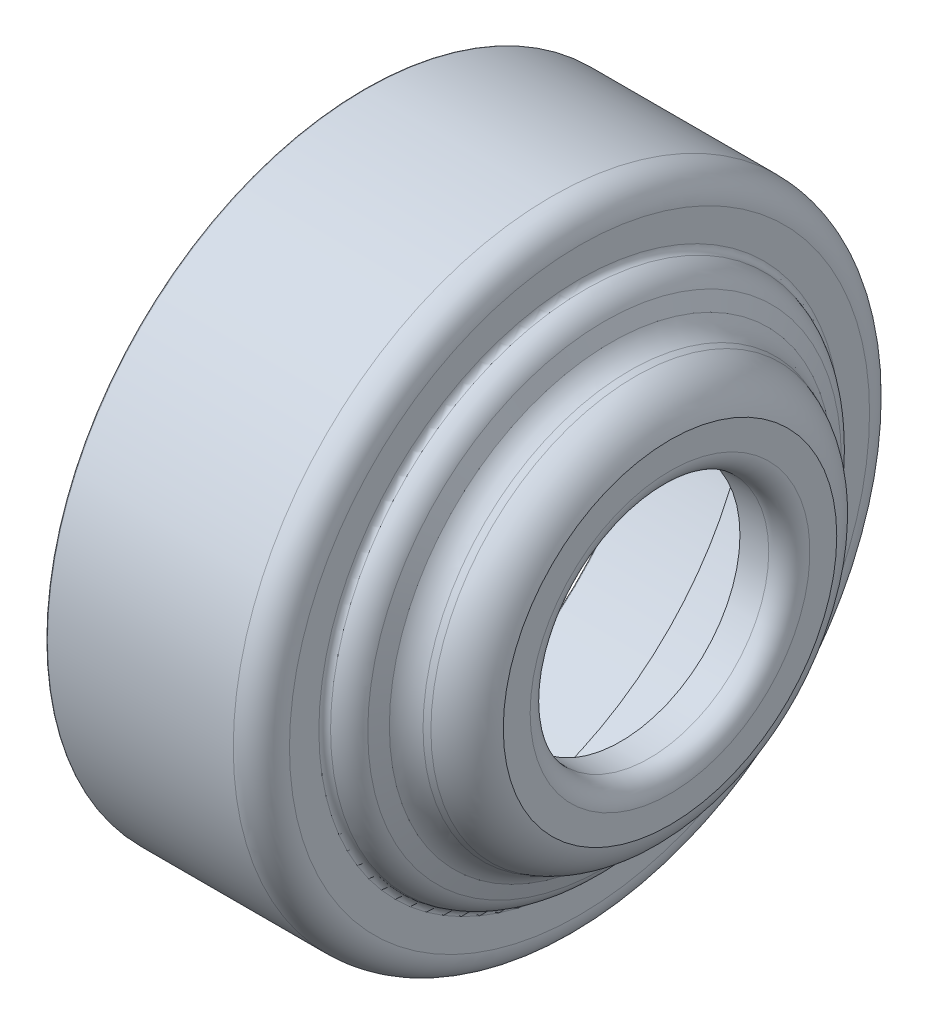
SolidWorks part; units mm, degrees
ref_plane "前视基准面" through (0, 0, 0) normal (0, 0, 1) x (1, 0, 0)
ref_plane "上视基准面" through (0, 0, 0) normal (0, 1, 0) x (1, 0, 0)
ref_plane "右视基准面" through (0, 0, 0) normal (1, 0, 0) x (0, 0, -1)
sketch "草图1" plane through (0, 0, 0) normal (0, 0, 1) x (1, 0, 0)
  line L0 (-28.9725, 0) -> (27.6414, 0) construction
  line L1 (0, 33.7643) -> (0, -22.2949) construction
  line L9 (-14.9, 22) -> (-7.9, 22)
  line L10 (-0.4, 20.9) -> (-0.4, 17.7)
  line L11 (-0.1, 17.4) -> (0.6, 17.4)
  line L12 (1.5207, 16.7949) -> (2.0219, 15.6141)
  line L13 (4.0243, 13.9299) -> (4.4661, 13.7651)
  line L14 (6.2, 12) -> (6.2, 9.9)
  line L15 (5.7, 9.4) -> (3.8, 9.4)
  line L17 (3.8, 9.4) -> (3.8, 8.7)
  line L18 (-14.9, 23.2) -> (-1.25, 23.2)
  line L19 (-0.4, 23.7801) -> (-0.4, -6.5039) construction
  line L20 (0.8, 21.15) -> (0.8, 19.0082)
  line L21 (-14.9, 23.2) -> (-14.9, 22)
  line L22 (2.6244, 17.2658) -> (3.0938, 16.1601)
  line L23 (4.4435, 15.0542) -> (4.8612, 14.8985)
  line L24 (7.4, 12.1596) -> (7.4, 10.2)
  line L26 (6.2, 12) -> (6.2, 10.9875) construction
  line L27 (0.8, 21.15) -> (0.8, 18.5911) construction
  line L28 (0.8, 18.5911) -> (0.8, 18.5911) construction
  line L29 (3.8, 9.4) -> (3.8, 9) construction
  line L30 (5.5608, 8.2) -> (4.6944, 8.2) construction
  line L31 (5.6477, 9.4) -> (3.8, 9.4) construction
  line L32 (4.6944, 8.2) -> (4.6944, 8.2) construction
  line L33 (7.4, 12.1596) -> (7.4, 11.5217) construction
  line L34 (-7.9, 22) -> (-7.9, 21.4)
  line L35 (-7.9, 21.4) -> (-0.9, 21.4)
  line L36 (-0.4, 21.15) -> (-0.4, 17.7) construction
  line L37 (3.8, 8.7) -> (5.9, 8.7)
  line L38 (-14.9, 22) -> (-1.25, 22) construction
  arc A8 (1.5207, 16.7949) -> (0.6, 17.4) centre (0.602, 16.4) ccw
  arc A9 (2.0219, 15.6141) -> (4.0243, 13.9299) centre (5.3857, 17.5808) ccw
  arc A10 (6.2, 12) -> (4.4661, 13.7651) centre (3.6572, 11.2364) ccw
  arc A12 (-0.1, 17.4) -> (-0.4, 17.7) centre (-0.1, 17.7) cw
  arc A13 (0.8, 21.15) -> (-1.25, 23.2) centre (-1.25, 21.15) ccw
  arc A14 (7.4, 11.5217) -> (5.5608, 8.2) centre (5.8037, 10.2356) cw construction
  arc A15 (2.6244, 17.2658) -> (1.1707, 18.5252) centre (0.602, 16.4) ccw
  arc A16 (3.0938, 16.1601) -> (4.4435, 15.0542) centre (5.3857, 17.5808) ccw
  arc A17 (7.4, 12.1596) -> (4.8612, 14.8985) centre (3.6572, 11.2364) ccw
  arc A19 (2.6244, 17.2658) -> (0.8, 18.5911) centre (0.602, 16.4) ccw construction
  arc A20 (0.8, 19.0082) -> (1.1707, 18.5252) centre (1.3, 19.0082) ccw
  arc A21 (0.8, 18.5911) -> (0.8, 18.5911) centre (0.8, 18.5911) cw construction
  arc A22 (6.2, 10.9875) -> (5.6477, 9.4) centre (5.8037, 10.2356) cw construction
  arc A23 (6.2, 9.9) -> (5.7, 9.4) centre (5.7, 9.9) cw
  arc A25 (-0.4, 21.15) -> (-1.25, 22) centre (-1.25, 21.15) ccw construction
  arc A26 (-0.4, 20.9) -> (-0.9, 21.4) centre (-0.9, 20.9) ccw
  arc A27 (5.9, 8.7) -> (7.4, 10.2) centre (5.9, 10.2) ccw
  point P15 (0, 22.4)
  point P24 (3, 14.5)
  point P27 (7, 13)
  point P30 (7, 9)
  point P61 (0, 0)
  point P66 (-7.9, 21.7)
  point P69 (7.4, 11.1798)
  point P71 (-0.4, -22.2949)
  dimension "D11" = 1.8
  dimension "D12" = 0.4
  dimension "D13" = 0.5
  dimension "D14" = 2.4
  dimension "D15" = 1.5
  dimension "D16" = 7.5
  dimension "D5" = 0.3
  dimension "D8" = 0.5
  dimension "D19" = 0.5
  dimension "D20" = 2.05
  dimension "D23" = 1
  dimension "D24" = 2.2
  dimension "D2" = 18.8
  dimension "D3" = 34.8
  dimension "D4" = 29
  dimension "D6" = 1.2
  dimension "D7" = 3
  dimension "D9" = 24
  dimension "D10" = 3.8
  dimension "D18" = 44
  dimension "D17" = 7
  dimension "D21" = 1.2
  dimension "D22" = 1.2
  dimension "D25" = 0.7
  dimension "D26" = 1
  dimension "D27" = 23
  dimension "D28" = 14.1
revolve "旋转1" add sketch "草图1" angle 360 about L0
fillet "圆角2" radius 0.1 2 edges at (-14.9, 0, 22) (-14.9, 0, 23.2)
